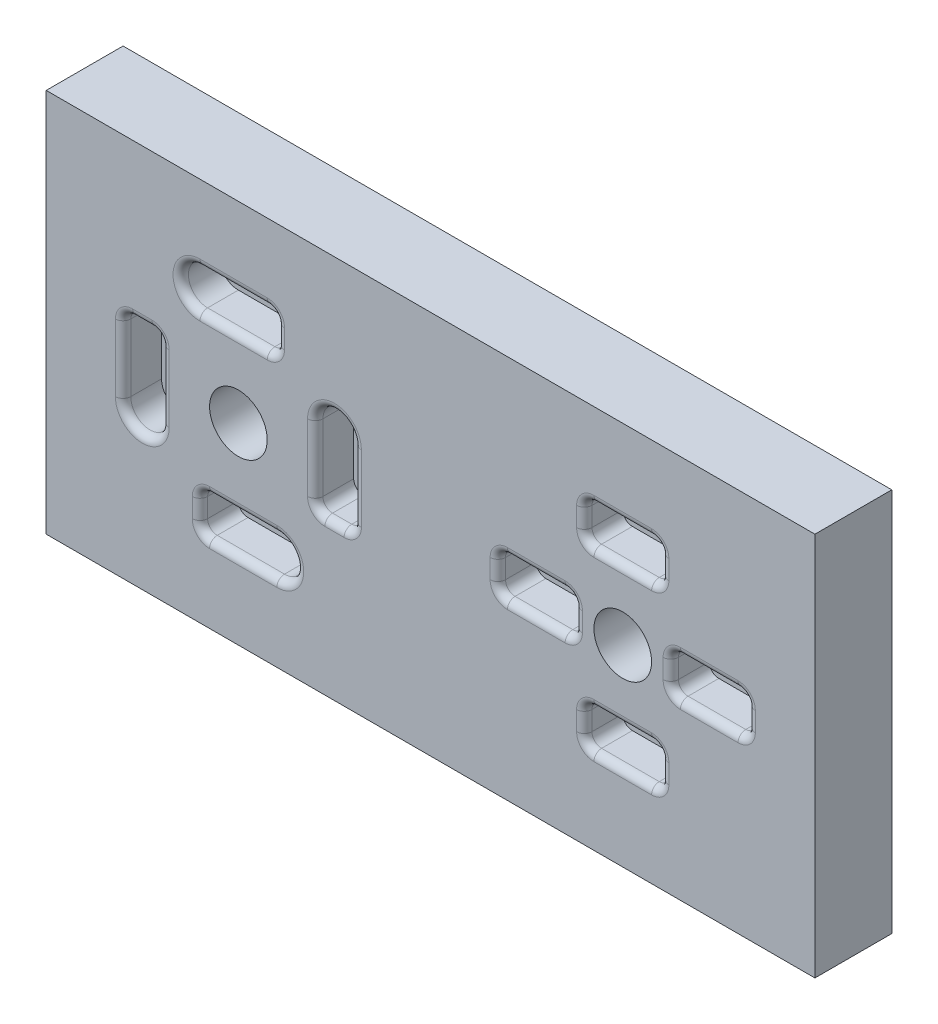
SolidWorks part; units mm, degrees
ref_plane "Front" through (0, 0, 0) normal (0, 0, 1) x (1, 0, 0)
ref_plane "Top" through (0, 0, 0) normal (0, 1, 0) x (1, 0, 0)
ref_plane "Right" through (0, 0, 0) normal (1, 0, 0) x (0, 0, -1)
sketch "Sketch1" plane through (0, 0, 0) normal (0, 0, 1) x (1, 0, 0)
  line L1 (0, 0) -> (254, 0)
  line L2 (0, 0) -> (0, 127)
  line L3 (0, 127) -> (254, 127)
  line L4 (254, 0) -> (254, 127)
  dimension "D1" = 254
  dimension "D2" = 127
extrude "Extrude1" add sketch "Sketch1" along normal blind 25.4
sketch "Sketch2" plane through (0, 0, 25.4) normal (0, 0, 1) x (1, 0, 0)
  line L0 (0, 127) -> (0, 0) construction
  line L1 (254, 0) -> (254, 127) construction
  line L2 (254, 127) -> (0, 127) construction
  circle A0 centre (63.5, 63.5) radius 9.525
  circle A1 centre (190.5, 63.5) radius 9.525
  dimension "D5" = 19.05
  dimension "D6" = 19.05
  dimension "D1" = 63.5
  dimension "D2" = 63.5
  dimension "D3" = 63.5
  dimension "D4" = 63.5
extrude "Cut-Extrude1" cut sketch "Sketch2" against normal blind 19.05
sketch "Sketch3" plane through (0, 0, 25.4) normal (0, 0, 1) x (1, 0, 0)
  line L0 (63.5, 63.5) -> (63.5, -19.0605) construction
  line L1 (50.8, 34.925) -> (50.8, 28.575)
  line L9 (53.975, 25.4) -> (76.2, 25.4)
  line L11 (53.975, 38.1) -> (76.2, 38.1)
  line L13 (101.6, 53.975) -> (101.6, 76.2)
  line L14 (88.9, 53.975) -> (88.9, 76.2)
  line L15 (98.425, 50.8) -> (92.075, 50.8)
  line L16 (73.025, 101.6) -> (50.8, 101.6)
  line L17 (73.025, 88.9) -> (50.8, 88.9)
  line L18 (76.2, 98.425) -> (76.2, 92.075)
  line L19 (25.4, 73.025) -> (25.4, 50.8)
  line L20 (38.1, 73.025) -> (38.1, 50.8)
  line L21 (28.575, 76.2) -> (34.925, 76.2)
  arc A8 (50.8, 34.925) -> (53.975, 38.1) centre (53.975, 34.925) cw
  arc A9 (50.8, 28.575) -> (53.975, 25.4) centre (53.975, 28.575) ccw
  arc A11 (76.2, 38.1) -> (76.2, 25.4) centre (76.2, 31.75) cw
  arc A12 (92.075, 50.8) -> (88.9, 53.975) centre (92.075, 53.975) cw
  arc A13 (98.425, 50.8) -> (101.6, 53.975) centre (98.425, 53.975) ccw
  arc A14 (88.9, 76.2) -> (101.6, 76.2) centre (95.25, 76.2) cw
  arc A15 (76.2, 92.075) -> (73.025, 88.9) centre (73.025, 92.075) cw
  arc A16 (76.2, 98.425) -> (73.025, 101.6) centre (73.025, 98.425) ccw
  arc A17 (50.8, 88.9) -> (50.8, 101.6) centre (50.8, 95.25) cw
  arc A18 (34.925, 76.2) -> (38.1, 73.025) centre (34.925, 73.025) cw
  arc A19 (28.575, 76.2) -> (25.4, 73.025) centre (28.575, 73.025) ccw
  arc A20 (38.1, 50.8) -> (25.4, 50.8) centre (31.75, 50.8) cw
extrude "Cut-Extrude2" cut sketch "Sketch3" against normal blind 12.7
fillet "Fillet2" radius 2.54
sketch "Sketch4" plane through (0, 0, 25.4) normal (0, 0, 1) x (1, 0, 0)
  line L0 (190.5, 63.5) -> (190.5, 18.4287) construction
  line L1 (203.2, 37.465) -> (203.2, 31.115)
  line L2 (180.975, 40.64) -> (200.025, 40.64)
  line L3 (177.8, 37.465) -> (177.8, 31.115)
  line L4 (180.975, 27.94) -> (200.025, 27.94)
  line L5 (190.5, 63.5) -> (249.2662, 63.5) construction
  line L6 (180.975, 99.06) -> (200.025, 99.06)
  line L7 (177.8, 89.535) -> (177.8, 95.885)
  line L8 (180.975, 86.36) -> (200.025, 86.36)
  line L9 (203.2, 89.535) -> (203.2, 95.885)
  line L10 (219.075, 80.7197) -> (219.075, 45.1749) construction
  line L11 (209.55, 69.85) -> (228.6, 69.85)
  line L12 (206.375, 66.675) -> (206.375, 60.325)
  line L13 (209.55, 57.15) -> (228.6, 57.15)
  line L14 (231.775, 66.675) -> (231.775, 60.325)
  line L15 (149.225, 66.675) -> (149.225, 60.325)
  line L16 (171.45, 57.15) -> (152.4, 57.15)
  line L17 (174.625, 66.675) -> (174.625, 60.325)
  line L18 (171.45, 69.85) -> (152.4, 69.85)
  circle A0 centre (190.5, 63.5) radius 9.525 construction
  arc A1 (200.025, 27.94) -> (203.2, 31.115) centre (200.025, 31.115) ccw
  arc A2 (180.975, 40.64) -> (177.8, 37.465) centre (180.975, 37.465) ccw
  arc A3 (177.8, 31.115) -> (180.975, 27.94) centre (180.975, 31.115) ccw
  arc A4 (200.025, 40.64) -> (203.2, 37.465) centre (200.025, 37.465) cw
  arc A5 (200.025, 86.36) -> (203.2, 89.535) centre (200.025, 89.535) ccw
  arc A6 (177.8, 95.885) -> (180.975, 99.06) centre (180.975, 95.885) cw
  arc A7 (180.975, 86.36) -> (177.8, 89.535) centre (180.975, 89.535) cw
  arc A8 (200.025, 99.06) -> (203.2, 95.885) centre (200.025, 95.885) cw
  arc A9 (228.6, 57.15) -> (231.775, 60.325) centre (228.6, 60.325) ccw
  arc A10 (228.6, 69.85) -> (231.775, 66.675) centre (228.6, 66.675) cw
  arc A11 (209.55, 69.85) -> (206.375, 66.675) centre (209.55, 66.675) ccw
  arc A12 (206.375, 60.325) -> (209.55, 57.15) centre (209.55, 60.325) ccw
  arc A13 (174.625, 60.325) -> (171.45, 57.15) centre (171.45, 60.325) cw
  arc A14 (171.45, 69.85) -> (174.625, 66.675) centre (171.45, 66.675) cw
  arc A15 (152.4, 69.85) -> (149.225, 66.675) centre (152.4, 66.675) ccw
  arc A16 (152.4, 57.15) -> (149.225, 60.325) centre (152.4, 60.325) cw
  dimension "D3" = 22.86
  dimension "D5" = 3.175
  dimension "D2" = 3.175
  dimension "D8" = 25.4
  dimension "D9" = 28.575
  dimension "D11" = 3.175
  dimension "D1" = 12.7
  dimension "D4" = 12.7
  dimension "D6" = 6.35
  dimension "D7" = 12.7
  dimension "D10" = 12.7
extrude "Cut-Extrude3" cut sketch "Sketch4" against normal blind 12.7
fillet "Fillet3" radius 2.54
sketch "Circular Sketch" plane through (0, 0, 25.4) normal (0, 0, 1) x (1, 0, 0)
  point P0 (180.975, 43.18)
  point P1 (209.55, 72.39)
  point P3 (180.975, 101.6)
  point P5 (152.4, 72.39)
